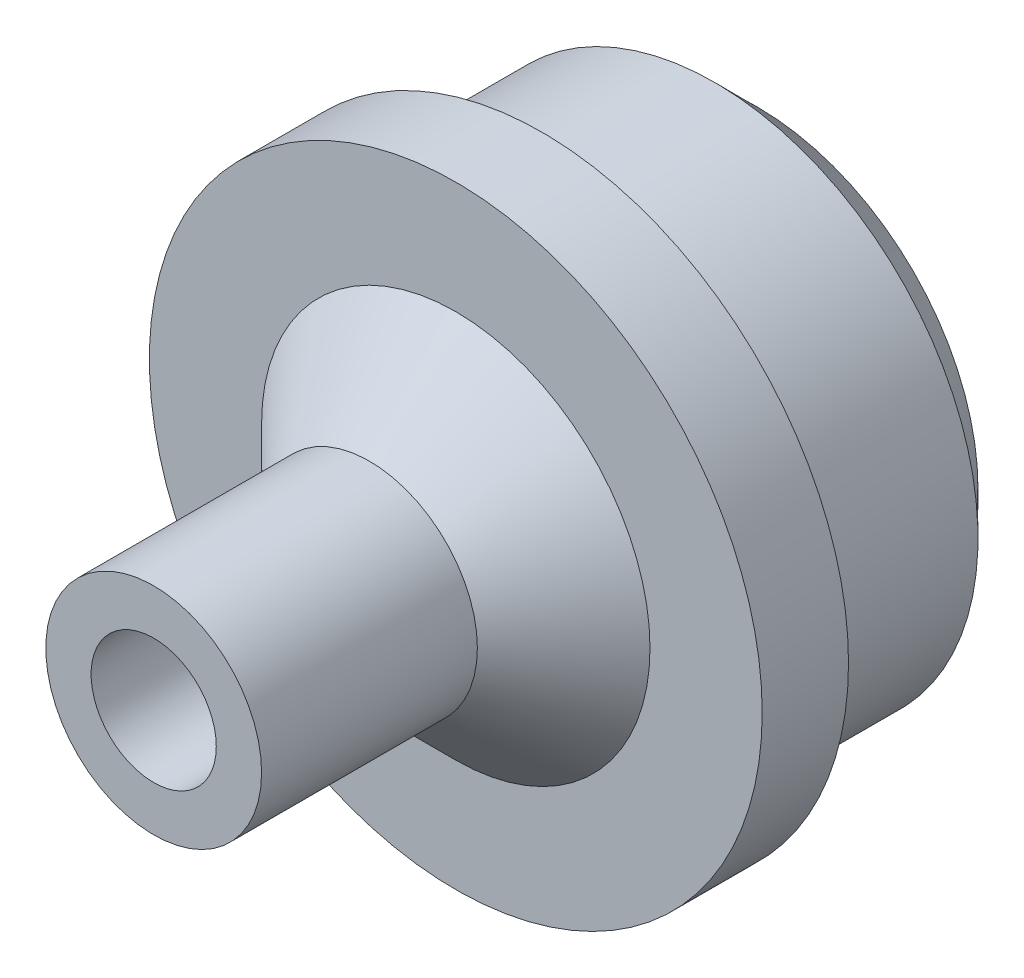
SolidWorks part; units mm, degrees
ref_plane "正面" through (0, 0, 0) normal (0, 0, 1) x (1, 0, 0)
ref_plane "平面" through (0, 0, 0) normal (0, 1, 0) x (1, 0, 0)
ref_plane "右側面" through (0, 0, 0) normal (1, 0, 0) x (0, 0, -1)
sketch "ｽｹｯﾁ1" plane through (0, 0, 0) normal (0, 0, 1) x (1, 0, 0)
  line L3 (-6.0369, 0.875) -> (-6.35, 0.875)
  line L4 (-6.35, -0.875) -> (-6.0369, -0.875)
  line L5 (-6.35, 0.875) -> (-6.35, -0.875)
  line L6 (-6.0369, 0.875) -> (-6.35, 0.875)
  line L7 (-6.35, -0.875) -> (-6.0369, -0.875)
  line L8 (-6.35, 0.875) -> (-6.35, -0.875)
  circle A1 centre (0, 0) radius 7.1
  circle A2 centre (0, 0) radius 7.1
  arc A3 (-6.0369, -0.875) -> (-6.0369, 0.875) centre (0, 0) ccw
  arc A4 (-6.0369, -0.875) -> (-6.0369, 0.875) centre (0, 0) ccw
  dimension "D1" = 0
  dimension "D2" = 0
extrude "ﾎﾞｽ - 押し出し1" add sketch "ｽｹｯﾁ1" against normal blind 5 contours L7 A4 L6 L8
sketch "ｽｹｯﾁ2" plane through (0, 0, 0) normal (0, 0, 1) x (1, 0, 0)
  circle A1 centre (0, 0) radius 7.1
  circle A2 centre (0, 0) radius 7.1
  dimension "D1" = 0
extrude "ﾎﾞｽ - 押し出し2" add sketch "ｽｹｯﾁ2" along normal blind 2
sketch "ｽｹｯﾁ3" plane through (0, 0, 2) normal (0, 0, 1) x (1, 0, 0)
  circle A0 centre (0, 0) radius 2.5
  dimension "D1" = 5
extrude "ﾎﾞｽ - 押し出し3" add sketch "ｽｹｯﾁ3" along normal blind 7
chamfer "面取り1" distance 2 angle 45 1 edges at (2.5, 0, 2)
sketch "ｽｹｯﾁ4" plane through (0, 0, 9) normal (0, 0, 1) x (1, 0, 0)
  circle A0 centre (0, 0) radius 1.45
  dimension "D1" = 2.9
extrude "ｶｯﾄ - 押し出し1" cut sketch "ｽｹｯﾁ4" against normal blind 30
chamfer "面取り2" distance 1 angle 45 1 edges at (6.1, 0, -5)
